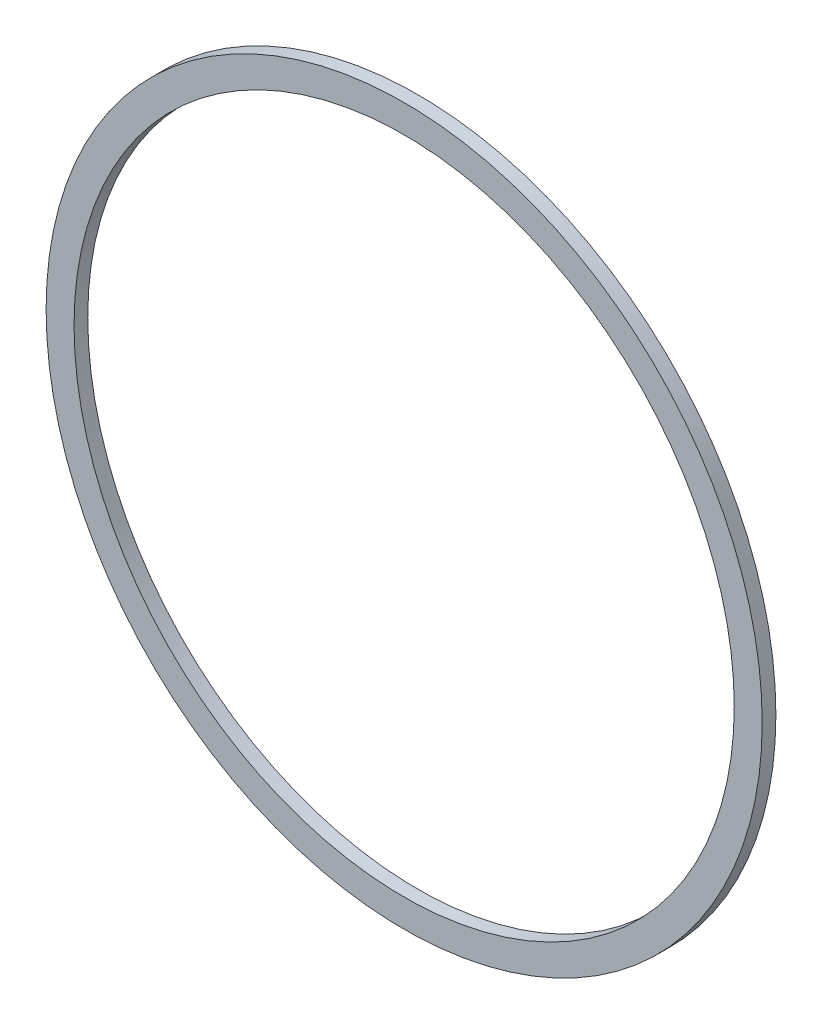
SolidWorks part; units mm, degrees
ref_plane "Front Plane" through (0, 0, 0) normal (0, 0, 1) x (1, 0, 0)
ref_plane "Top Plane" through (0, 0, 0) normal (0, 1, 0) x (1, 0, 0)
ref_plane "Right Plane" through (0, 0, 0) normal (1, 0, 0) x (0, 0, -1)
sketch "Sketch1" plane through (0, 0, 0) normal (0, 0, 1) x (1, 0, 0)
  circle A0 centre (0, 0) radius 82.9945
  dimension "D1" = 165.989
extrude "Boss-Extrude1" add sketch "Sketch1" along normal blind 3.175
sketch "Sketch2" plane through (0, 0, 0) normal (0, 0, -1) x (-1, 0, 0)
  circle A0 centre (0, 0) radius 76.5175
  dimension "D1" = 153.035
extrude "Cut-Extrude1" cut sketch "Sketch2" against normal through all
